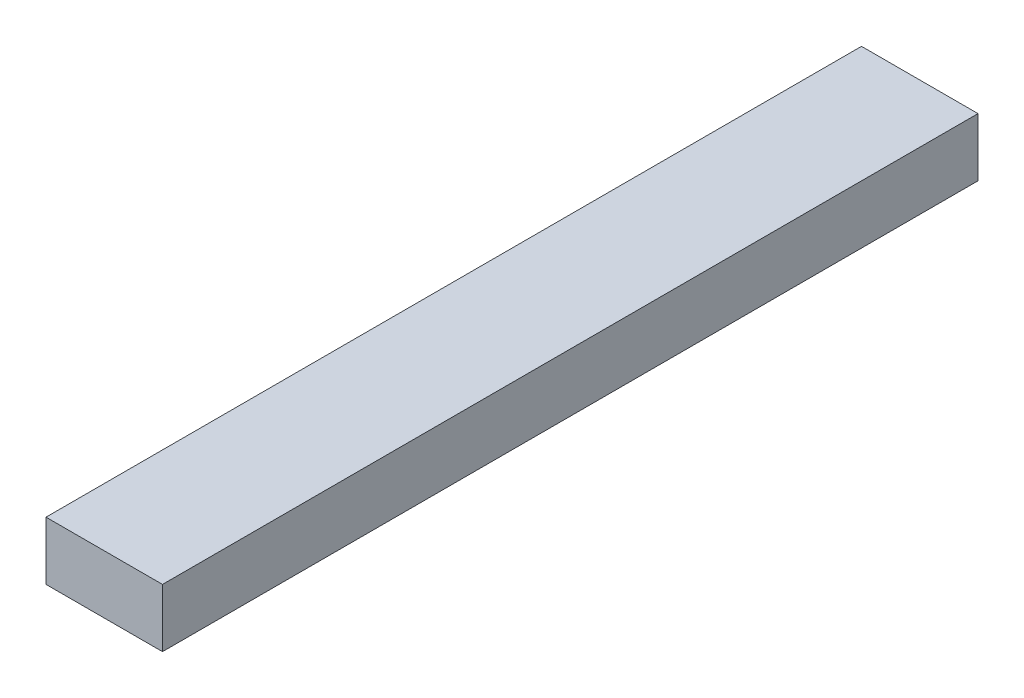
SolidWorks part; units mm, degrees
ref_plane "Front" through (0, 0, 0) normal (0, 0, 1) x (1, 0, 0)
ref_plane "Top" through (0, 0, 0) normal (0, 1, 0) x (1, 0, 0)
ref_plane "Right" through (0, 0, 0) normal (1, 0, 0) x (0, 0, -1)
sketch "草图1" plane through (0, 0, 0) normal (0, 0, 1) x (1, 0, 0)
  line L1 (-30.2031, 10.9908) -> (20.5969, 10.9908)
  line L2 (-30.2031, 10.9908) -> (-30.2031, -14.4092)
  line L3 (-30.2031, -14.4092) -> (20.5969, -14.4092)
  line L4 (20.5969, 10.9908) -> (20.5969, -14.4092)
  dimension "D1" = 50.8
  dimension "D2" = 25.4
extrude "凸台-拉伸1" add sketch "草图1" along normal blind 355.6
